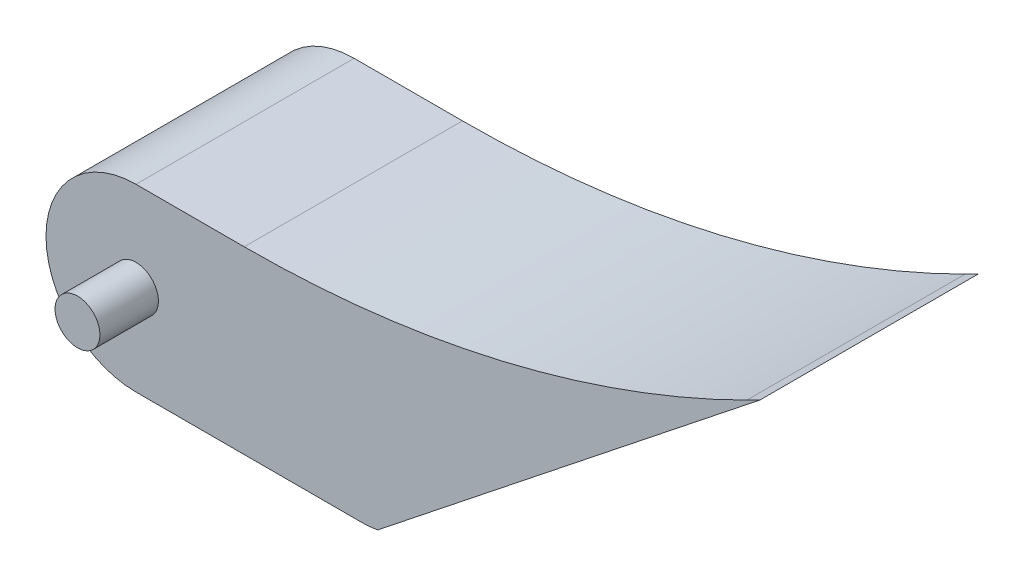
SolidWorks part; units mm, degrees
ref_plane "Alzado" through (0, 0, 0) normal (0, 0, 1) x (1, 0, 0)
ref_plane "Planta" through (0, 0, 0) normal (0, 1, 0) x (1, 0, 0)
ref_plane "Vista lateral" through (0, 0, 0) normal (1, 0, 0) x (0, 0, -1)
sketch "Croquis1" plane through (0, 0, 0) normal (0, 0, 1) x (1, 0, 0)
  line L0 (0, 40) -> (100.1808, 40)
  line L1 (0, -40) -> (100.1808, -40)
  line L4 (132.6859, 23.3114) -> (277.3559, 95.5881)
  line L5 (277.3559, 95.5881) -> (107.5034, -39.324)
  arc A0 (0, 40) -> (0, -40) centre (0, 0) ccw
  arc A1 (100.1808, -40) -> (107.5034, -39.324) centre (100.1808, 0) ccw
  arc A2 (132.6859, 23.3114) -> (100.1808, 40) centre (100.1808, 0) ccw
extrude "Saliente-Extruir2" add sketch "Croquis1" along normal blind 97
fillet "Redondeo2" radius 500 1 edges at (132.6859, 23.3114, 48.5)
sketch "Croquis2" plane through (0, 0, 0) normal (0, 0, -1) x (-1, 0, 0)
  circle A0 centre (0, 0) radius 9.966
extrude "Saliente-Extruir3" add sketch "Croquis2" along normal blind 26 and the other way blind 123
